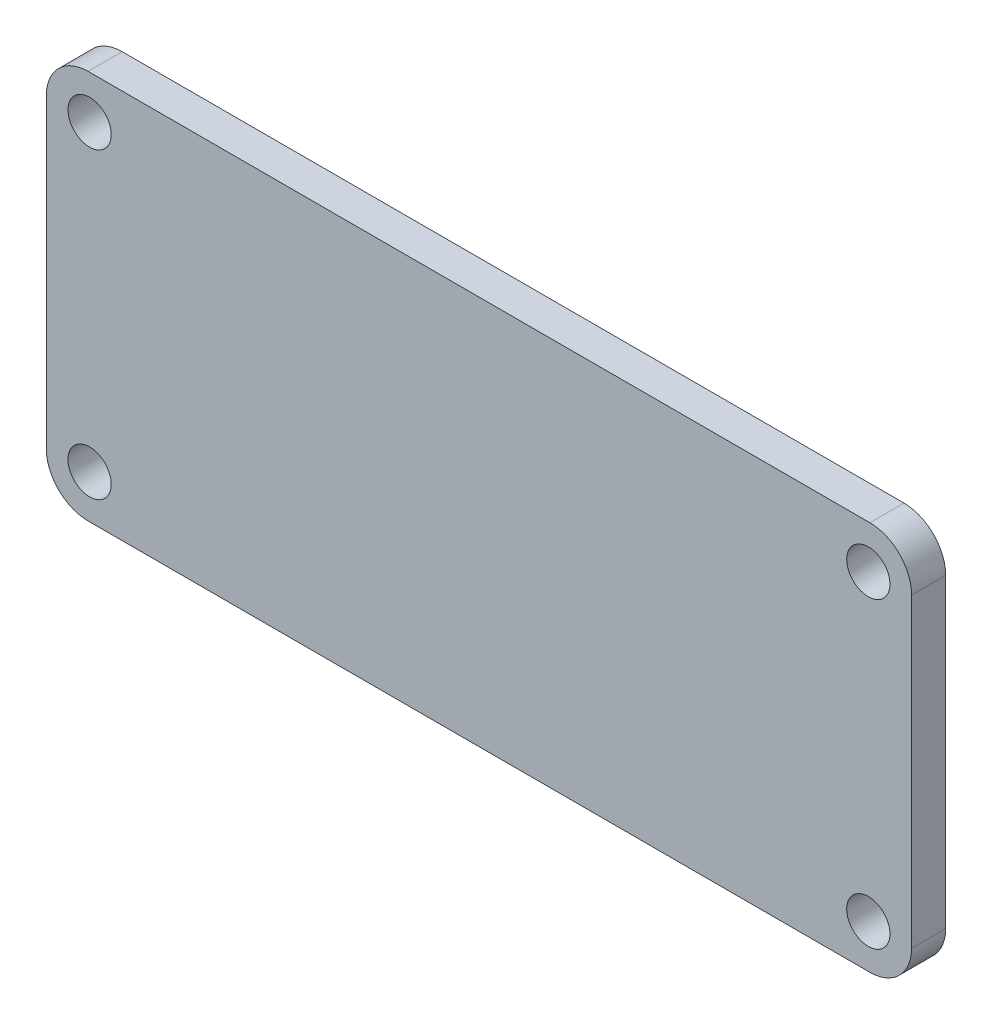
SolidWorks part; units mm, degrees
ref_plane "Alzado" through (0, 0, 0) normal (0, 0, 1) x (1, 0, 0)
ref_plane "Planta" through (0, 0, 0) normal (0, 1, 0) x (1, 0, 0)
ref_plane "Vista lateral" through (0, 0, 0) normal (1, 0, 0) x (0, 0, -1)
sketch "Croquis1" plane through (0, 0, 0) normal (0, 0, 1) x (1, 0, 0)
  line L0 (-25.4, 0) -> (25.4, 0) construction
  line L1 (22.95, -11.43) -> (-22.95, -11.43)
  line L2 (25.4, -8.98) -> (25.4, 8.98)
  line L3 (22.95, 11.43) -> (-22.95, 11.43)
  line L4 (-25.4, -8.98) -> (-25.4, 8.98)
  line L5 (25.4, -11.43) -> (-25.4, 11.43) construction
  line L6 (25.4, 11.43) -> (-25.4, -11.43) construction
  line L7 (0, 11.43) -> (0, -11.43) construction
  circle A0 centre (-22.86, 8.89) radius 1.27
  circle A1 centre (-22.86, -8.89) radius 1.27
  circle A2 centre (22.86, -8.89) radius 1.27
  circle A3 centre (22.86, 8.89) radius 1.27
  arc A4 (25.4, 8.98) -> (22.95, 11.43) centre (22.95, 8.98) ccw
  arc A5 (25.4, -8.98) -> (22.95, -11.43) centre (22.95, -8.98) cw
  arc A6 (-22.95, -11.43) -> (-25.4, -8.98) centre (-22.95, -8.98) cw
  arc A7 (-22.95, 11.43) -> (-25.4, 8.98) centre (-22.95, 8.98) ccw
  point P0 (0, 0)
  dimension "D4" = 22.86
  dimension "D5" = 2.54
  dimension "D6" = 2.45
  dimension "D1" = 50.8
  dimension "D2" = 22.86
  dimension "D3" = 8.89
extrude "Saliente-Extruir1" add sketch "Croquis1" along normal blind 2
